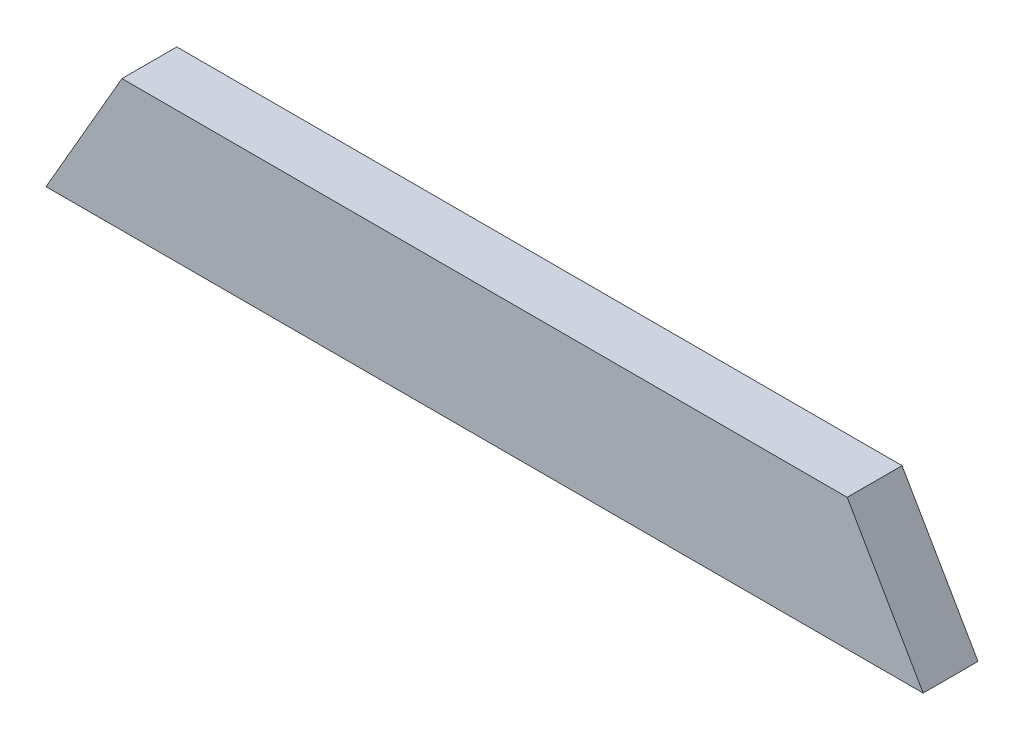
SolidWorks part; units mm, degrees
ref_plane "Plan de face" through (0, 0, 0) normal (0, 0, 1) x (1, 0, 0)
ref_plane "Plan de dessus" through (0, 0, 0) normal (0, 1, 0) x (1, 0, 0)
ref_plane "Plan de droite" through (0, 0, 0) normal (1, 0, 0) x (0, 0, -1)
sketch "Esquisse1" plane through (0, 0, 0) normal (0, 0, 1) x (1, 0, 0)
  line L0 (-200, 0) -> (200, 0)
  line L1 (200, 0) -> (165.359, 60)
  line L2 (165.359, 60) -> (-165.359, 60)
  line L3 (0, 60) -> (0, 0) construction
  line L4 (-200, 0) -> (-165.359, 60)
  dimension "D1" = 400
  dimension "D2" = 60
  dimension "D3" = 60
extrude "Boss.-Extru.1" add sketch "Esquisse1" along normal blind 25
